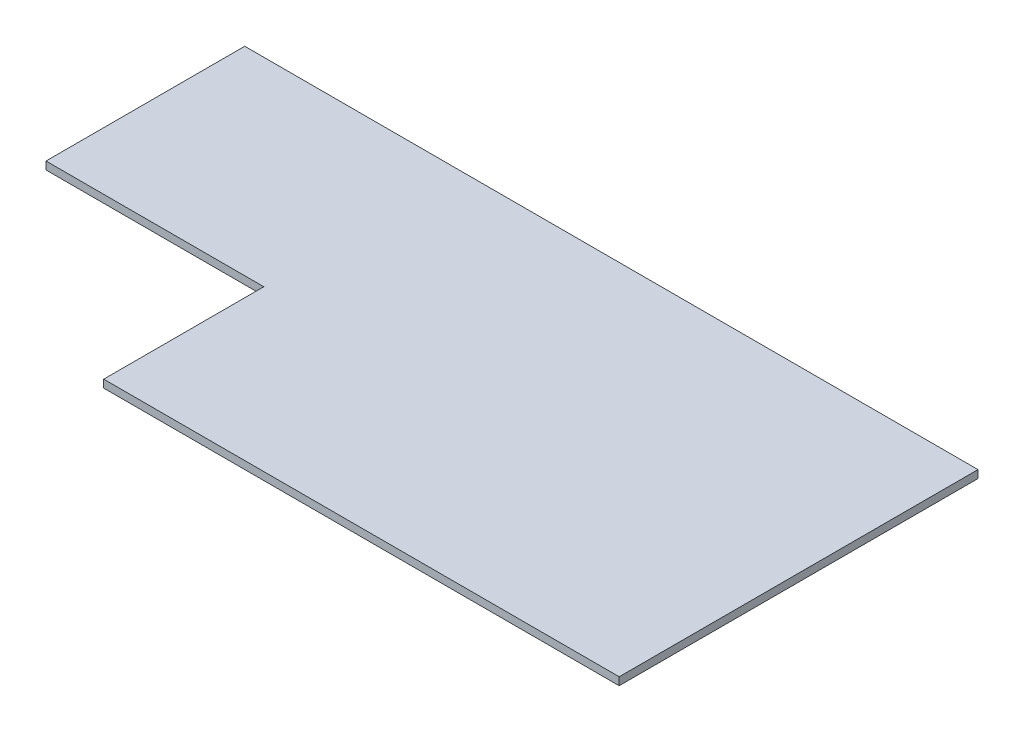
SolidWorks part; units mm, degrees
material "Acrylic (Medium-high impact)"
ref_plane "Front Plane" through (0, 0, 0) normal (0, 0, 1) x (1, 0, 0)
ref_plane "Top Plane" through (0, 0, 0) normal (0, 1, 0) x (1, 0, 0)
ref_plane "Right Plane" through (0, 0, 0) normal (1, 0, 0) x (0, 0, -1)
sketch "Sketch1" plane through (0, 0, 0) normal (0, 1, 0) x (1, 0, 0)
  line L1 (-123.5869, -144.8614) -> (296.0211, -144.8614)
  line L2 (-300.8789, -14.5594) -> (-300.8789, 147.2386)
  line L3 (-300.8789, 147.2386) -> (296.0211, 147.2386)
  line L4 (296.0211, -144.8614) -> (296.0211, 147.2386)
  line L5 (-285.9037, -142.2063) -> (296.0211, 147.2386) construction
  line L6 (-300.8789, 147.2386) -> (296.0211, -144.8614) construction
  line L9 (-300.8789, -14.5594) -> (-123.5869, -14.5594)
  line L10 (-123.5869, -144.8614) -> (-123.5869, -14.5594)
  point P0 (0, 0)
  dimension "D1" = 596.9
  dimension "D2" = 292.1
  dimension "D3" = 177.292
  dimension "D4" = 130.302
extrude "Boss-Extrude1" add sketch "Sketch1" along normal mid plane 6.35
